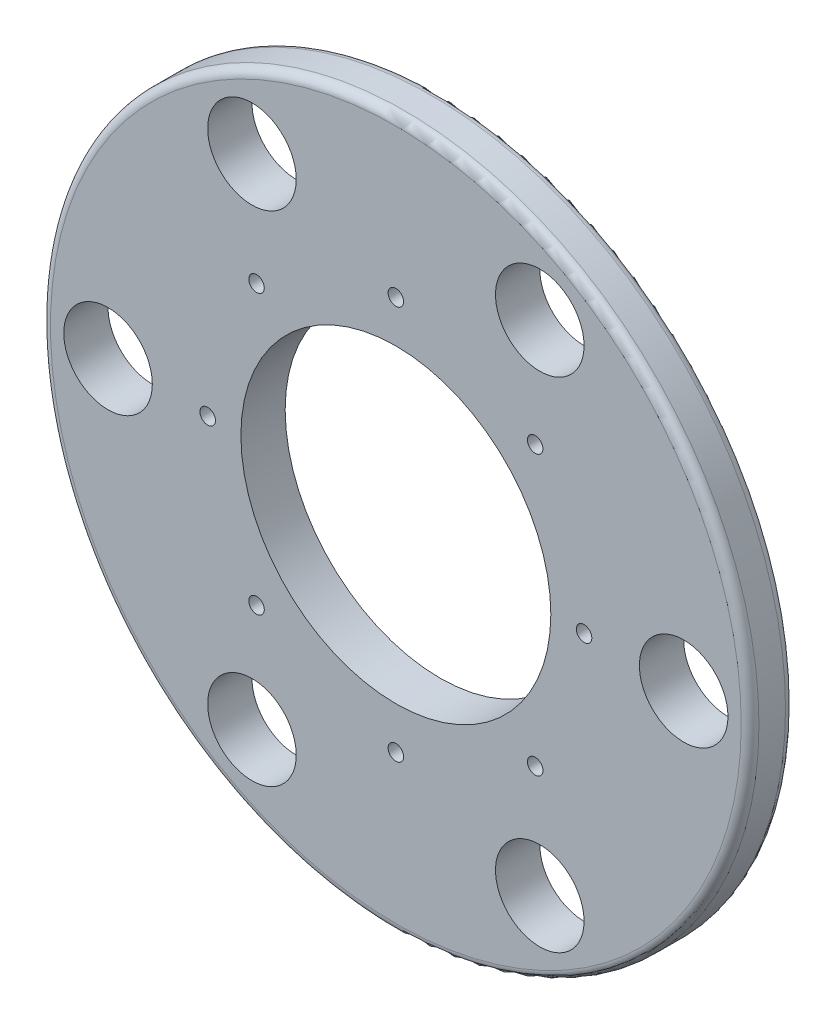
SolidWorks part; units mm, degrees
ref_plane "前视基准面" through (0, 0, 0) normal (0, 0, 1) x (1, 0, 0)
ref_plane "上视基准面" through (0, 0, 0) normal (0, 1, 0) x (1, 0, 0)
ref_plane "右视基准面" through (0, 0, 0) normal (1, 0, 0) x (0, 0, -1)
sketch "草图1" plane through (0, 0, 0) normal (0, 0, 1) x (1, 0, 0)
  line L2 (93.8169, 0) -> (107.4459, -5.5686)
  line L3 (107.4459, -5.5686) -> (107.6524, -5.9816)
  circle A0 centre (0, 0) radius 80
  circle A1 centre (0, 0) radius 29.5 construction
  circle A2 centre (0, 0) radius 44.5 construction
  circle A3 centre (-42.5, 0) radius 1.75
  circle A6 centre (42.5, 0) radius 1.75
  circle A9 centre (-21.25, 36.8061) radius 1.75
  circle A10 centre (21.25, 36.8061) radius 1.75
  circle A11 centre (-21.25, -36.8061) radius 1.75
  circle A12 centre (21.25, -36.8061) radius 1.75
  circle A14 centre (-22.25, 38.5381) radius 1.75
  circle A15 centre (22.25, 38.5381) radius 1.75
  circle A17 centre (22.25, -38.5381) radius 1.75
  circle A18 centre (-22.25, -38.5381) radius 1.75
  circle A19 centre (0, 0) radius 29.5
  point P25 (0, 0)
  point P38 (0, 0)
  dimension "D1" = 160
  dimension "D2" = 89
  dimension "D3" = 59
  dimension "D4" = 3.5
  dimension "D6" = 6
sketch "草图2" plane through (0, 0, 0) normal (0, 0, 1) x (1, 0, 0)
  circle A0 centre (0, 0) radius 48.25
  dimension "D1" = 96.5
sketch "草图3" plane through (0, 0, 0) normal (0, 0, 1) x (1, 0, 0)
  circle A0 centre (0, 0) radius 80
extrude "凸台-拉伸1" add sketch "草图3" against normal blind 10
sketch "草图4" plane through (0, 0, 0) normal (0, 0, 1) x (1, 0, 0)
  circle A0 centre (0, 0) radius 35
  dimension "D1" = 70
extrude "切除-拉伸1" cut sketch "草图4" against normal blind 7
sketch "草图5" plane through (0, 0, 0) normal (0, 0, 1) x (1, 0, 0)
  line L0 (0, 0) -> (-48.25, 0)
  circle A4 centre (-42.5, 0) radius 1.75
  circle A11 centre (0, 0) radius 48.25 construction
  circle A14 centre (-31.4663, 31.4663) radius 1.75
  circle A15 centre (0, 44.5) radius 1.75
  circle A16 centre (31.4663, 31.4663) radius 1.75
  circle A18 centre (31.4663, -31.4663) radius 1.75
  circle A19 centre (0, -44.5) radius 1.75
  circle A20 centre (-31.4663, -31.4663) radius 1.75
  circle A21 centre (42.5, 0) radius 1.75
  point P41 (0, 0)
sketch "草图6" plane through (0, 0, 0) normal (0, 0, 1) x (1, 0, 0)
  line L0 (0, 0) -> (-80, 0)
  circle A0 centre (0, 0) radius 80 construction
  circle A1 centre (-65, 0) radius 10
  circle A2 centre (-32.5, 56.2917) radius 10
  circle A3 centre (32.5, 56.2917) radius 10
  circle A4 centre (65, 0) radius 10
  circle A5 centre (32.5, -56.2917) radius 10
  circle A6 centre (-32.5, -56.2917) radius 10
  point P20 (0, 0)
  dimension "D1" = 20
  dimension "D2" = 15
  dimension "D3" = 6
extrude "切除-拉伸3" cut sketch "草图6" against normal blind 10 contours A2 | L0 A1 | L0 A1 | A6 | A5 | A4 | A3
extrude "切除-拉伸4" cut sketch "草图5" against normal blind 10 contours A15 | A16 | A21 | A18 | A20 | L0 A4 | L0 A4 | A14 | A19
sketch "草图7" plane through (0, 0, 0) normal (0, 0, 1) x (1, 0, 0)
  circle A0 centre (0, 0) radius 35
extrude "切除-拉伸5" cut sketch "草图7" against normal mid plane 40
fillet "圆角1" radius 2 2 edges at (80, 0, -10) (80, 0, 0)
